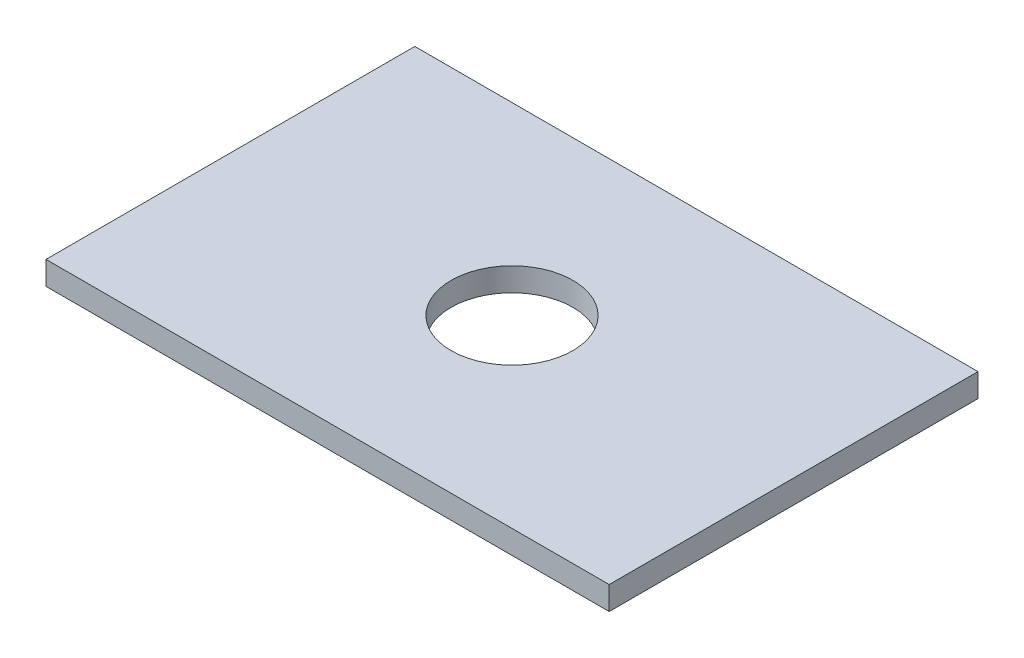
SolidWorks part; units mm, degrees
material "Oak"
ref_plane "Front Plane" through (0, 0, 0) normal (0, 0, 1) x (1, 0, 0)
ref_plane "Top Plane" through (0, 0, 0) normal (0, 1, 0) x (1, 0, 0)
ref_plane "Right Plane" through (0, 0, 0) normal (1, 0, 0) x (0, 0, -1)
sketch "Sketch1" plane through (0, 0, 0) normal (0, 1, 0) x (1, 0, 0)
  line L1 (0, 0) -> (152.7, 0)
  line L2 (0, 0) -> (0, 100)
  line L3 (0, 100) -> (152.7, 100)
  line L4 (152.7, 0) -> (152.7, 100)
  dimension "D1" = 152.7
  dimension "D2" = 100
extrude "Boss-Extrude1" add sketch "Sketch1" along normal blind 6.35
sketch "Sketch2" plane through (0, 6.35, 0) normal (0, 1, 0) x (1, 0, 0)
  line L0 (76.35, 100) -> (76.35, 0) construction
  line L1 (152.7, 100) -> (0, 100) construction
  line L2 (0, 0) -> (152.7, 0) construction
  line L3 (0, 50) -> (152.7, 50) construction
  line L4 (0, 100) -> (0, 0) construction
  line L5 (152.7, 0) -> (152.7, 100) construction
  circle A0 centre (76.35, 50) radius 16.51
  dimension "D1" = 33.02
extrude "Cut-Extrude1" cut sketch "Sketch2" against normal blind 10
